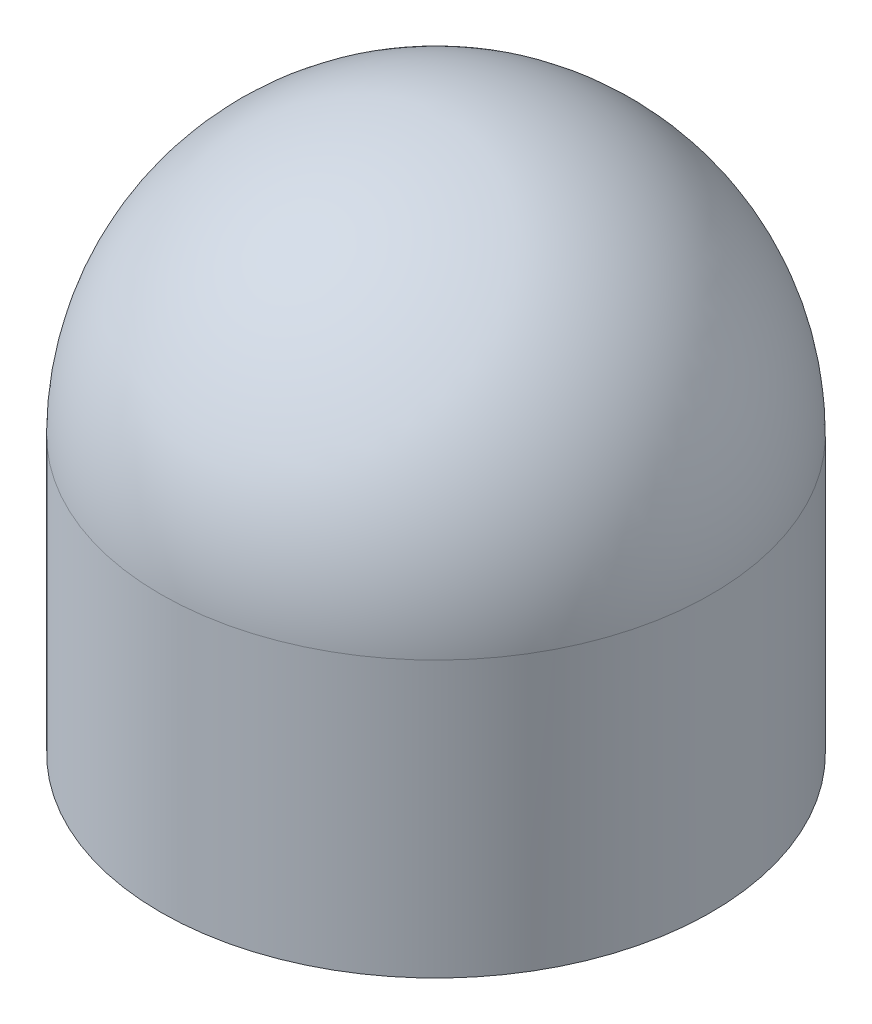
SolidWorks part; units mm, degrees
ref_plane "Front Plane" through (0, 0, 0) normal (0, 0, 1) x (1, 0, 0)
ref_plane "Top Plane" through (0, 0, 0) normal (0, 1, 0) x (1, 0, 0)
ref_plane "Right Plane" through (0, 0, 0) normal (1, 0, 0) x (0, 0, -1)
sketch "Sketch1" plane through (0, 0, 0) normal (1, 0, 0) x (0, 0, -1)
  line L0 (88.9, 0) -> (88.9, 88.9)
  line L1 (0, 177.8) -> (0, 0) construction
  line L2 (0, 177.8) -> (-68.903, 177.8) construction
  line L3 (0, 0) -> (88.9, 0) construction
  arc A0 (88.9, 88.9) -> (0, 177.8) centre (0, 88.9) ccw
  dimension "D1" = 88.9
  dimension "D2" = 177.8
revolve "Revolve-Thin1" add sketch "Sketch1" angle 360 about L1 wall 6.35
